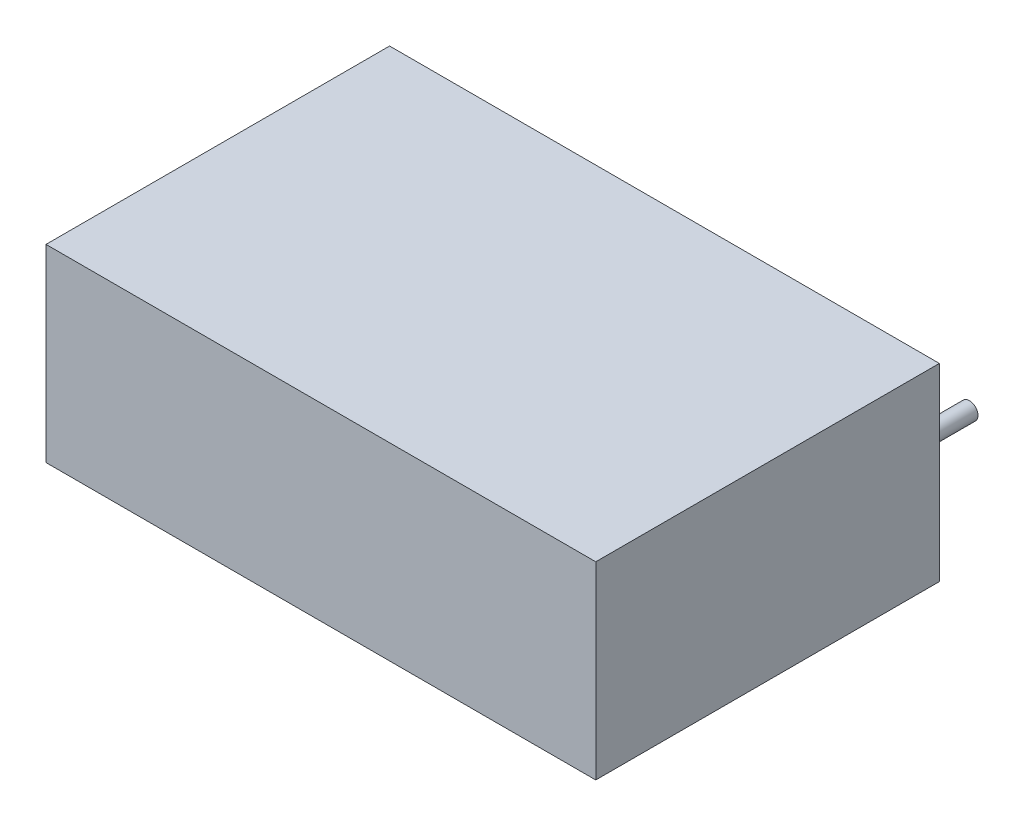
SolidWorks part; units mm, degrees
ref_plane "Front" through (0, 0, 0) normal (0, 0, 1) x (1, 0, 0)
ref_plane "Top" through (0, 0, 0) normal (0, 1, 0) x (1, 0, 0)
ref_plane "Right" through (0, 0, 0) normal (1, 0, 0) x (0, 0, -1)
sketch "Эскиз1" plane through (0, 0, 0) normal (0, 0, 1) x (1, 0, 0)
  line L1 (-0.8, -0.8) -> (0.8, -0.8)
  line L2 (-0.8, -0.8) -> (-0.8, 0.8)
  line L3 (-0.8, 0.8) -> (0.8, 0.8)
  line L4 (0.8, -0.8) -> (0.8, 0.8)
  line L5 (11.65, -0.8) -> (13.25, -0.8)
  line L6 (11.65, -0.8) -> (11.65, 0.8)
  line L7 (11.65, 0.8) -> (13.25, 0.8)
  line L8 (13.25, -0.8) -> (13.25, 0.8)
sketch "Эскиз2" plane through (0, 0, 0) normal (0, 0, 1) x (1, 0, 0)
  line L0 (-0.5, 5.5) -> (-0.5, -5.5)
  line L1 (31.5, -5.5) -> (31.5, 5.5)
  line L2 (-0.5, -5.5) -> (31.5, -5.5)
  line L3 (31.5, 5.5) -> (-0.5, 5.5)
  dimension "D1" = 32
  dimension "D2" = 11
  dimension "D3" = 5.5
  dimension "D4" = 0.5
extrude "Вытянуть1" add sketch "Эскиз2" along normal blind 20
sketch "Эскиз3" plane through (0, 0, 0) normal (0, 0, -1) x (-1, 0, 0)
  line L0 (-15.5, 10.0175) -> (-15.5, -10.945) construction
  line L1 (-32.2826, 0) -> (4.828, 0) construction
  line L2 (-31.5, 5.5) -> (0.5, 5.5) construction
  line L3 (0.5, -5.5) -> (-31.5, -5.5) construction
  line L4 (-31.5, -5.5) -> (-31.5, 5.5) construction
  line L5 (0.5, 5.5) -> (0.5, -5.5) construction
  circle A0 centre (-1.75, 0) radius 0.5
  circle A1 centre (-29.25, 0) radius 0.5
  dimension "D1" = 27.5
extrude "Вытянуть2" add sketch "Эскиз3" along normal blind 4
